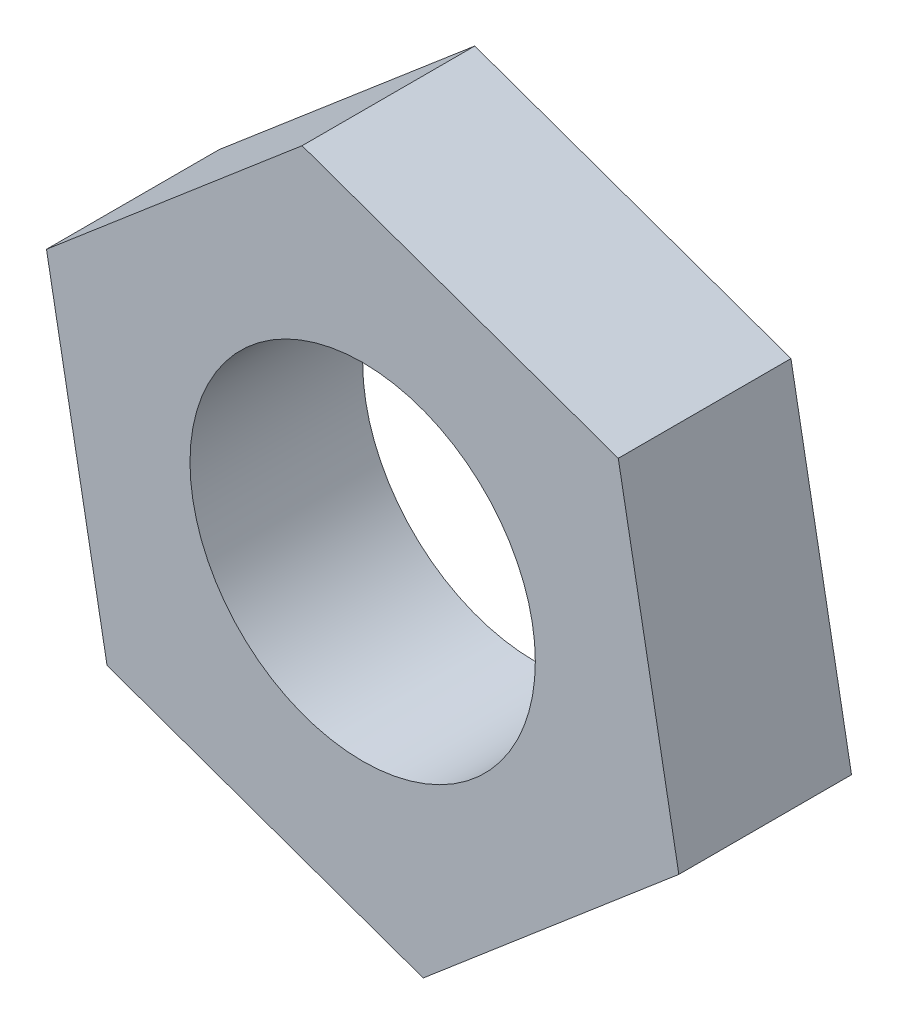
SolidWorks part; units mm, degrees
ref_plane "Front Plane" through (0, 0, 0) normal (0, 0, 1) x (1, 0, 0)
ref_plane "Top Plane" through (0, 0, 0) normal (0, 1, 0) x (1, 0, 0)
ref_plane "Right Plane" through (0, 0, 0) normal (1, 0, 0) x (0, 0, -1)
sketch "Sketch1" plane through (0, 0, 0) normal (0, 0, 1) x (1, 0, 0)
  line L1 (1324.4991, -1696.9218) -> (1328.9401, -1693.1429)
  line L2 (1328.9401, -1693.1429) -> (1327.8881, -1687.4074)
  line L3 (1327.8881, -1687.4074) -> (1322.3949, -1685.4507)
  line L4 (1322.3949, -1685.4507) -> (1317.9538, -1689.2296)
  line L5 (1317.9538, -1689.2296) -> (1319.0059, -1694.9652)
  line L6 (1324.1558, -1686.1863) -> (1322.7382, -1686.1863)
  line L7 (1319.4713, -1688.0724) -> (1318.7625, -1689.3001)
  line L8 (1318.7625, -1693.0724) -> (1319.4713, -1694.3001)
  line L9 (1322.7382, -1696.1863) -> (1324.1558, -1696.1863)
  line L10 (1327.4227, -1694.3001) -> (1328.1315, -1693.0724)
  line L11 (1328.1315, -1689.3001) -> (1327.4227, -1688.0724)
  line L12 (1324.1558, -1686.1863) -> (1322.7382, -1686.1863)
  line L13 (1319.4713, -1688.0724) -> (1318.7625, -1689.3001)
  line L14 (1318.7625, -1693.0724) -> (1319.4713, -1694.3001)
  line L15 (1322.7382, -1696.1863) -> (1324.1558, -1696.1863)
  line L16 (1327.4227, -1694.3001) -> (1328.1315, -1693.0724)
  line L17 (1328.1315, -1689.3001) -> (1327.4227, -1688.0724)
  line L18 (1319.0059, -1694.9652) -> (1324.4991, -1696.9218)
  arc A0 (1327.4227, -1688.0724) -> (1324.1558, -1686.1863) centre (1323.447, -1691.1863) ccw
  arc A1 (1322.7382, -1686.1863) -> (1319.4713, -1688.0724) centre (1323.447, -1691.1863) ccw
  arc A2 (1318.7625, -1689.3001) -> (1318.7625, -1693.0724) centre (1323.447, -1691.1863) ccw
  arc A3 (1319.4713, -1694.3001) -> (1322.7382, -1696.1863) centre (1323.447, -1691.1863) ccw
  arc A4 (1324.1558, -1696.1863) -> (1327.4227, -1694.3001) centre (1323.447, -1691.1863) ccw
  arc A5 (1328.1315, -1693.0724) -> (1328.1315, -1689.3001) centre (1323.447, -1691.1863) ccw
  arc A6 (1327.4227, -1688.0724) -> (1324.1558, -1686.1863) centre (1323.447, -1691.1863) ccw
  arc A7 (1322.7382, -1686.1863) -> (1319.4713, -1688.0724) centre (1323.447, -1691.1863) ccw
  arc A8 (1318.7625, -1689.3001) -> (1318.7625, -1693.0724) centre (1323.447, -1691.1863) ccw
  arc A9 (1319.4713, -1694.3001) -> (1322.7382, -1696.1863) centre (1323.447, -1691.1863) ccw
  arc A10 (1324.1558, -1696.1863) -> (1327.4227, -1694.3001) centre (1323.447, -1691.1863) ccw
  arc A11 (1328.1315, -1693.0724) -> (1328.1315, -1689.3001) centre (1323.447, -1691.1863) ccw
  circle A12 centre (1323.447, -1691.1863) radius 5.05 construction
  circle A13 centre (1323.447, -1691.1863) radius 3
  dimension "D2" = 6
  dimension "D1" = 0
extrude "Boss-Extrude1" add sketch "Sketch1" against normal blind 3 contours A11 L17 A6 L12 A7 L13 A8 L14 A9 L15 A10 L16 A13 | A10 L15 A9 L18 L1 | A11 L16 A10 L1 L2 | A11 L2 L3 A6 L17 | A7 L12 A6 L3 L4 | A8 L13 A7 L4 L5 | A9 L14 A8 L5 L18
